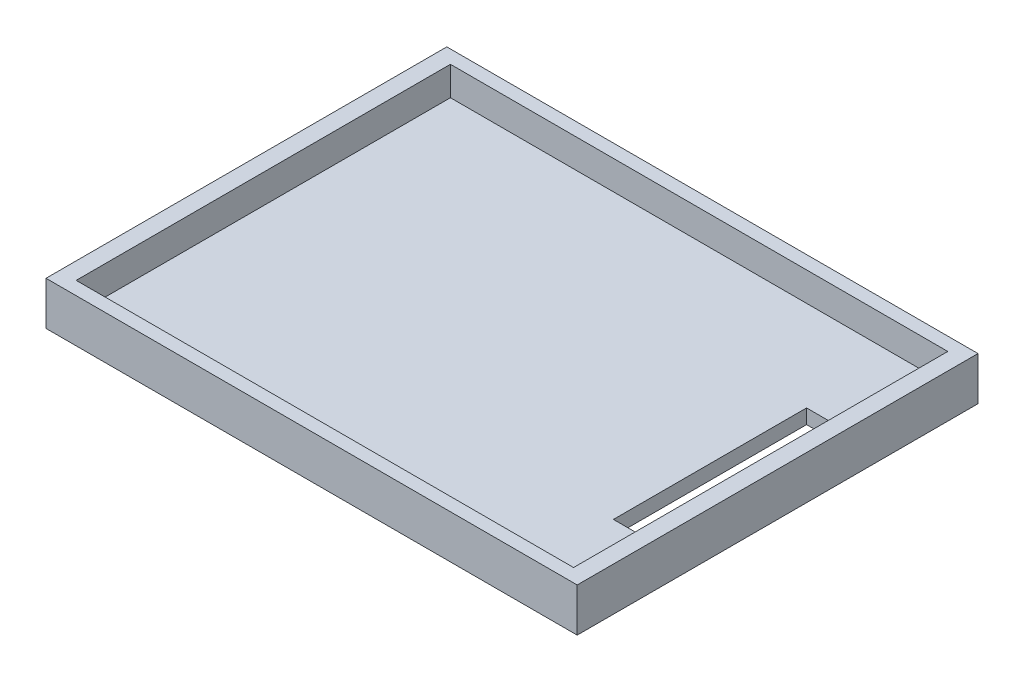
SolidWorks part; units mm, degrees
ref_plane "Front Plane" through (0, 0, 0) normal (0, 0, 1) x (1, 0, 0)
ref_plane "Top Plane" through (0, 0, 0) normal (0, 1, 0) x (1, 0, 0)
ref_plane "Right Plane" through (0, 0, 0) normal (1, 0, 0) x (0, 0, -1)
sketch "Sketch2" plane through (0, 0, 0) normal (0, 1, 0) x (1, 0, 0)
  line L0 (-55, 41.5) -> (55, -41.5) construction
  line L1 (-55, 41.5) -> (55, 41.5)
  line L2 (-55, 41.5) -> (-55, -41.5)
  line L3 (-55, -41.5) -> (55, -41.5)
  line L4 (55, 41.5) -> (55, -41.5)
  line L5 (-55, -41.5) -> (55, 41.5) construction
  line L6 (-55, 0) -> (55, 0) construction
  line L21 (51, 20) -> (41, 20)
  line L22 (41, 20) -> (41, -20)
  line L23 (41, -20) -> (51, -20)
  line L24 (51, -20) -> (51, 20)
  point P9 (0, 0)
  point P15 (41, 0)
  dimension "D1" = 110
  dimension "D2" = 83
  dimension "D3" = 40
  dimension "D4" = 10
  dimension "D5" = 4
extrude "Boss-Extrude1" add sketch "Sketch2" along normal blind 9
sketch "Sketch4" plane through (0, 9, 0) normal (0, 1, 0) x (1, 0, 0)
  line L1 (-51.5, 38.75) -> (51.5, 38.75)
  line L2 (-51.5, 38.75) -> (-51.5, -38.75)
  line L3 (-51.5, -38.75) -> (51.5, -38.75)
  line L4 (51.5, 38.75) -> (51.5, -38.75)
  line L5 (-51.5, 38.75) -> (51.5, -38.75) construction
  line L6 (-51.5, -38.75) -> (51.5, 38.75) construction
  line L7 (-55, 41.5) -> (55, -41.5) construction
  point P0 (0, 0)
  point P13 (0, 0)
  dimension "D1" = 103
  dimension "D2" = 77.5
extrude "Cut-Extrude1" cut sketch "Sketch4" against normal blind 6
ref_plane "Plane2" through (-1.75, 0, 0) normal (-1, 0, 0) x (0, 0, 1)
sketch "Sketch12" plane through (-1.75, 0, 0) normal (-1, 0, 0) x (0, 0, 1)
  line L0 (-41.5, 9) -> (-41.5, 20.3895)
  line L1 (-41.5, 20.3895) -> (41.2241, 20.3895)
  line L2 (41.2241, 20.3895) -> (41.5, 9)
  line L3 (41.5, 9) -> (-41.5, 9)
